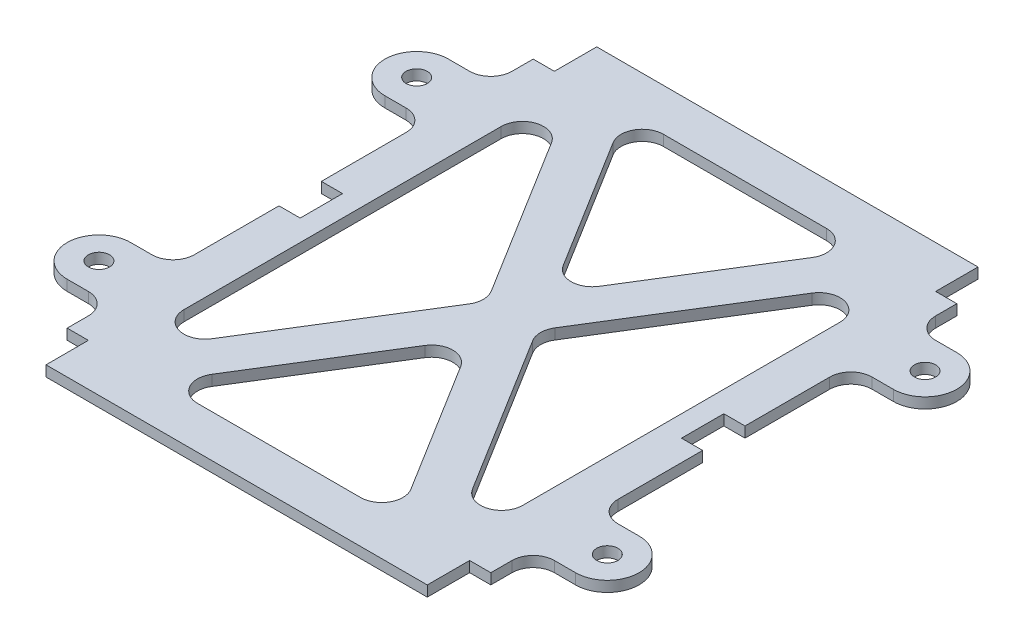
SolidWorks part; units mm, degrees
ref_plane "Front Plane" through (0, 0, 0) normal (0, 0, 1) x (1, 0, 0)
ref_plane "Top Plane" through (0, 0, 0) normal (0, 1, 0) x (1, 0, 0)
ref_plane "Right Plane" through (0, 0, 0) normal (1, 0, 0) x (0, 0, -1)
sketch "Sketch1" plane through (0, 0, 0) normal (0, 1, 0) x (1, 0, 0)
  line L0 (107.95, 78.6193) -> (64.6224, 78.6193) construction
  line L6 (107.95, 126.1857) -> (107.95, 31.053)
  line L7 (0, 161.1693) -> (114.3, 161.1693)
  line L8 (-6.35, 148.4693) -> (-6.35, 142.1193)
  line L9 (0, -3.9307) -> (114.3, -3.9307)
  line L10 (120.65, 148.4693) -> (120.65, 142.1193)
  line L11 (81.5938, 8.7693) -> (32.7062, 8.7693)
  line L12 (6.35, 126.1857) -> (6.35, 31.053)
  line L13 (-12.7, 135.7693) -> (-19.05, 135.7693)
  line L15 (-12.7, 116.7193) -> (-19.05, 116.7193)
  line L17 (96.2038, 27.7058) -> (66.6987, 75.2721)
  line L18 (127, 135.7693) -> (133.35, 135.7693)
  line L20 (127, 116.7193) -> (133.35, 116.7193)
  line L22 (127, 40.5193) -> (133.35, 40.5193)
  line L23 (127, 21.4693) -> (133.35, 21.4693)
  line L24 (-12.7, 21.4693) -> (-19.05, 21.4693)
  line L26 (-12.7, 40.5193) -> (-19.05, 40.5193)
  line L27 (-6.35, 110.3693) -> (-6.35, 84.9693)
  line L28 (-6.35, 15.1193) -> (-6.35, 8.7693)
  line L29 (120.65, 15.1193) -> (120.65, 8.7693)
  line L30 (120.65, 110.3693) -> (120.65, 84.9693)
  line L31 (96.2038, 129.5329) -> (66.6987, 81.9666)
  line L32 (86.99, 138.7721) -> (62.5462, 99.3653)
  line L33 (86.99, 18.4666) -> (62.5462, 57.8734)
  line L34 (51.7538, 99.3653) -> (27.31, 138.7721)
  line L35 (49.6776, 78.6193) -> (6.35, 78.6193) construction
  line L36 (47.6013, 81.9666) -> (18.0962, 129.5329)
  line L37 (47.6013, 75.2721) -> (18.0962, 27.7058)
  line L38 (51.7538, 57.8734) -> (27.31, 18.4666)
  line L39 (57.15, 76.2) -> (57.15, 161.1693) construction
  line L42 (120.65, 8.7693) -> (114.3, 8.7693)
  line L43 (114.3, -3.9307) -> (114.3, 8.7693)
  line L44 (-6.35, 8.7693) -> (0, 8.7693)
  line L45 (0, -3.9307) -> (0, 8.7693)
  line L48 (120.65, 148.4693) -> (114.3, 148.4693)
  line L49 (114.3, 161.1693) -> (114.3, 148.4693)
  line L53 (0, 161.1693) -> (0, 148.4693)
  line L54 (-6.35, 148.4693) -> (0, 148.4693)
  line L56 (81.5938, 148.4693) -> (32.7062, 148.4693)
  line L57 (114.3, 78.6193) -> (0, 78.6193) construction
  line L58 (120.65, 72.2693) -> (120.65, 46.8693)
  line L59 (120.65, 72.2693) -> (114.3, 72.2693)
  line L61 (120.65, 84.9693) -> (114.3, 84.9693)
  line L62 (114.3, 72.2693) -> (114.3, 84.9693)
  line L63 (-6.35, 84.9693) -> (0, 84.9693)
  line L64 (0, 72.2693) -> (0, 84.9693)
  line L65 (-6.35, 72.2693) -> (0, 72.2693)
  line L66 (-6.35, 72.2693) -> (-6.35, 46.8693)
  arc A0 (-19.05, 135.7693) -> (-19.05, 116.7193) centre (-19.05, 126.2443) ccw
  arc A1 (133.35, 135.7693) -> (133.35, 116.7193) centre (133.35, 126.2443) cw
  arc A2 (133.35, 21.4693) -> (133.35, 40.5193) centre (133.35, 30.9943) ccw
  arc A3 (-19.05, 21.4693) -> (-19.05, 40.5193) centre (-19.05, 30.9943) cw
  arc A4 (120.65, 15.1193) -> (127, 21.4693) centre (127, 15.1193) cw
  arc A5 (120.65, 46.8693) -> (127, 40.5193) centre (127, 46.8693) ccw
  arc A6 (120.65, 110.3693) -> (127, 116.7193) centre (127, 110.3693) cw
  arc A7 (127, 135.7693) -> (120.65, 142.1193) centre (127, 142.1193) cw
  arc A8 (-12.7, 21.4693) -> (-6.35, 15.1193) centre (-12.7, 15.1193) cw
  arc A9 (-12.7, 40.5193) -> (-6.35, 46.8693) centre (-12.7, 46.8693) ccw
  arc A10 (-6.35, 110.3693) -> (-12.7, 116.7193) centre (-12.7, 110.3693) ccw
  arc A11 (-12.7, 135.7693) -> (-6.35, 142.1193) centre (-12.7, 142.1193) ccw
  circle A12 centre (-19.05, 126.2443) radius 3.175
  circle A13 centre (-19.05, 30.9943) radius 3.175
  circle A14 centre (133.35, 30.9943) radius 3.175
  circle A15 centre (133.35, 126.2443) radius 3.175
  arc A16 (6.35, 126.1857) -> (18.0962, 129.5329) centre (12.7, 126.1857) cw
  arc A17 (47.6013, 75.2721) -> (47.6013, 81.9666) centre (42.2051, 78.6193) ccw
  arc A18 (18.0962, 27.7058) -> (6.35, 31.053) centre (12.7, 31.053) cw
  arc A19 (32.7062, 8.7693) -> (27.31, 18.4666) centre (32.7062, 15.1193) cw
  arc A20 (86.99, 18.4666) -> (81.5938, 8.7693) centre (81.5938, 15.1193) cw
  arc A21 (62.5462, 57.8734) -> (51.7538, 57.8734) centre (57.15, 54.5262) ccw
  arc A22 (51.7538, 99.3653) -> (62.5462, 99.3653) centre (57.15, 102.7125) ccw
  arc A23 (32.7062, 148.4693) -> (27.31, 138.7721) centre (32.7062, 142.1193) ccw
  arc A24 (86.99, 138.7721) -> (81.5938, 148.4693) centre (81.5938, 142.1193) ccw
  arc A25 (66.6987, 75.2721) -> (66.6987, 81.9666) centre (72.0949, 78.6193) cw
  arc A26 (107.95, 31.053) -> (96.2038, 27.7058) centre (101.6, 31.053) cw
  arc A27 (96.2038, 129.5329) -> (107.95, 126.1857) centre (101.6, 126.1857) cw
  point P5 (57.15, 76.2)
  point P39 (-6.35, 116.7193)
  point P42 (-6.35, 135.7693)
  point P54 (6.35, 148.4693)
  point P69 (6.35, 8.7693)
  point P72 (21.2949, 8.7693)
  point P75 (93.0051, 8.7693)
  point P78 (57.15, 66.5728)
  point P83 (21.2949, 148.4693)
  point P86 (93.0051, 148.4693)
  point P92 (107.95, 8.7693)
  point P95 (107.95, 148.4693)
  dimension "D5" = 19.05
  dimension "D13" = 9.525
  dimension "D14" = 9.525
  dimension "D15" = 9.525
  dimension "D16" = 6.35
  dimension "D17" = 6.35
  dimension "D18" = 6.35
  dimension "D23" = 6.35
  dimension "D1" = 19.05
  dimension "D2" = 19.05
  dimension "D3" = 6.35
  dimension "D4" = 12.7
  dimension "D6" = 12.7
  dimension "D7" = 12.7
  dimension "D8" = 19.05
  dimension "D9" = 25.4
  dimension "D10" = 25.4
  dimension "D11" = 25.4
  dimension "D12" = 25.4
  dimension "D19" = 12.7
  dimension "D20" = 12.7
  dimension "D21" = 12.7
  dimension "D22" = 12.7
  dimension "D24" = 6.35
  dimension "D25" = 12.7
  dimension "D26" = 82.55
extrude "Boss-Extrude1" add sketch "Sketch1" along normal blind 3.175
